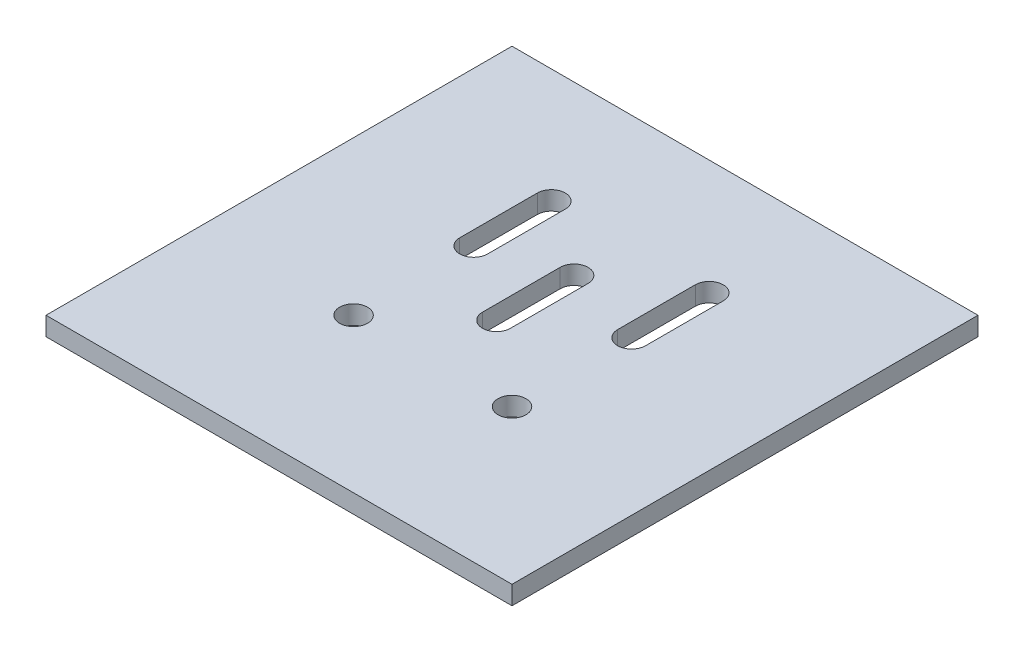
SolidWorks part; units mm, degrees
ref_plane "Front Plane" through (0, 0, 0) normal (0, 0, 1) x (1, 0, 0)
ref_plane "Top Plane" through (0, 0, 0) normal (0, 1, 0) x (1, 0, 0)
ref_plane "Right Plane" through (0, 0, 0) normal (1, 0, 0) x (0, 0, -1)
sketch "Sketch1" plane through (0, 0, 0) normal (0, 1, 0) x (1, 0, 0)
  line L0 (-8.5, 8.5) -> (8.5, 8.5) construction
  line L1 (-25, -25) -> (25, -25)
  line L2 (-25, -25) -> (-25, 25)
  line L3 (-25, 25) -> (25, 25)
  line L4 (25, -25) -> (25, 25)
  line L5 (8.5, 8.5) -> (8.5, -8.5) construction
  line L6 (-10.002, 4.3905) -> (-10.002, 12.7191)
  line L8 (7, 4.3357) -> (7, 12.6643)
  line L10 (10, 4.3357) -> (10, 12.6643)
  line L11 (7, 4.3357) -> (10, 12.6643) construction
  line L12 (7, 12.6643) -> (10, 4.3357) construction
  line L13 (-7.002, 4.3905) -> (-7.002, 12.7191)
  line L14 (-7.002, 12.7191) -> (-9.998, 4.2809) construction
  line L15 (-9.998, 4.2809) -> (-7.002, 4.3905) construction
  line L16 (-10.002, 12.7191) -> (-7.002, 4.3905) construction
  line L17 (-1.8708, -1.2939) -> (-1.8708, 7.0347)
  line L18 (1.1292, -1.2939) -> (1.1292, 7.0347)
  circle A2 centre (8.5, -8.5) radius 1.5
  circle A3 centre (-8.5, -8.5) radius 1.5
  arc A4 (10, 12.6643) -> (7, 12.6643) centre (8.5, 12.6643) ccw
  arc A5 (10, 4.3357) -> (7, 4.3357) centre (8.5, 4.3357) cw
  arc A6 (-7.002, 12.7191) -> (-10.002, 12.7191) centre (-8.502, 12.7191) ccw
  arc A7 (-7.002, 4.3905) -> (-10.002, 4.3905) centre (-8.502, 4.3905) cw
  arc A8 (1.1292, 7.0347) -> (-1.8708, 7.0347) centre (-0.3708, 7.0347) ccw
  arc A9 (1.1292, -1.2939) -> (-1.8708, -1.2939) centre (-0.3708, -1.2939) cw
  point P0 (0, 0)
  point P14 (8.5, 0)
  point P17 (0, 8.5)
  point P18 (0, 25)
  point P19 (25, 0)
  point P25 (-8.5, 8.5)
  dimension "D2" = 17
  dimension "D3" = 17
  dimension "D4" = 50
  dimension "D5" = 3
extrude "Boss-Extrude1" add sketch "Sketch1" along normal blind 2
